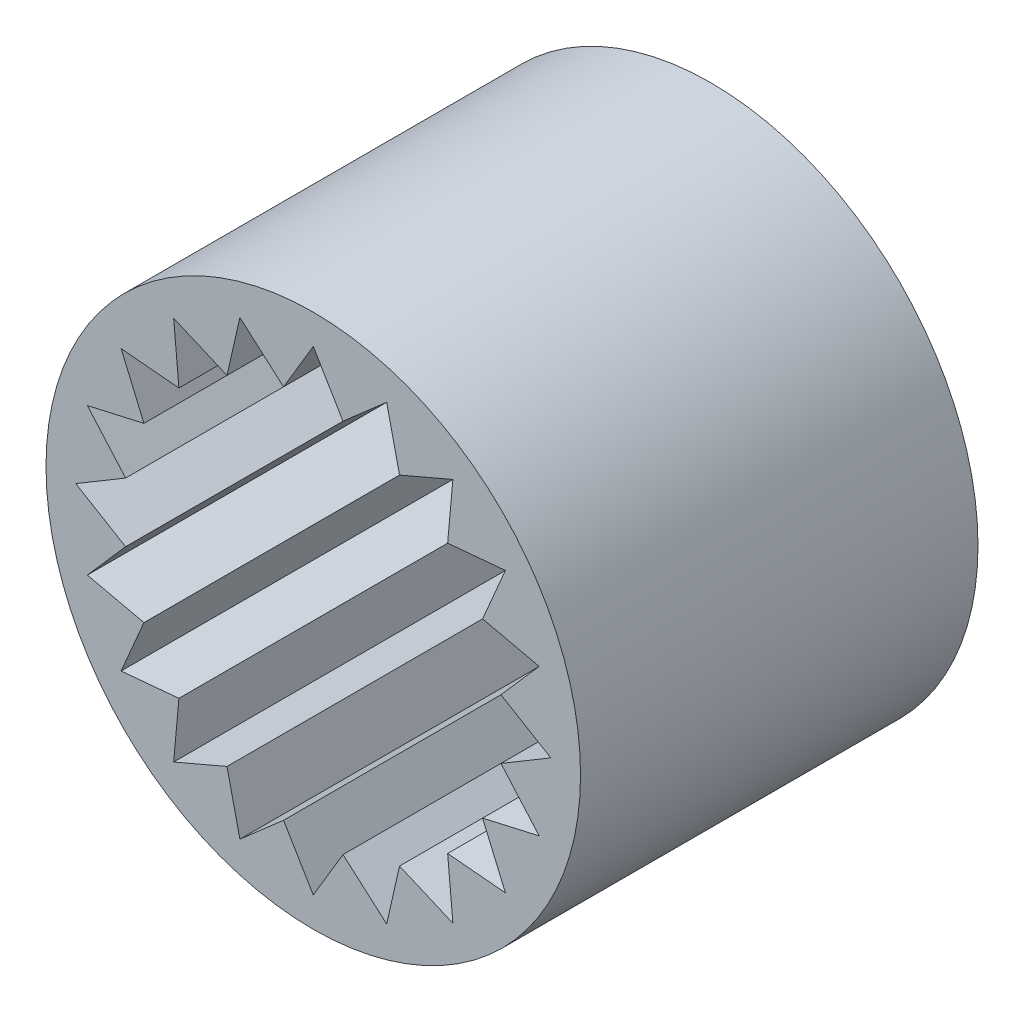
SolidWorks part; units mm, degrees
ref_plane "Front Plane" through (0, 0, 0) normal (0, 0, 1) x (1, 0, 0)
ref_plane "Top Plane" through (0, 0, 0) normal (0, 1, 0) x (1, 0, 0)
ref_plane "Right Plane" through (0, 0, 0) normal (1, 0, 0) x (0, 0, -1)
sketch "ServoSplineProfile" plane through (0, 0, 0) normal (0, 0, 1) x (1, 0, 0)
  line L0 (0, 0) -> (0, 2.5) construction
  line L1 (0, 0) -> (0.7725, 2.3776) construction
  line L2 (0, 0) -> (0.3911, 2.4692) construction
  line L3 (0, 2.5) -> (0.3129, 1.9754) construction
  line L4 (0.3129, 1.9754) -> (0.7725, 2.3776) construction
  line L5 (0.7725, 2.3776) -> (0.908, 1.782) construction
  line L6 (0.908, 1.782) -> (1.4695, 2.0225) construction
  line L7 (1.4695, 2.0225) -> (1.4142, 1.4142) construction
  line L8 (1.4142, 1.4142) -> (2.0225, 1.4695) construction
  line L9 (2.0225, 1.4695) -> (1.782, 0.908) construction
  line L10 (1.782, 0.908) -> (2.3776, 0.7725) construction
  line L11 (2.3776, 0.7725) -> (1.9754, 0.3129) construction
  line L12 (1.9754, 0.3129) -> (2.5, 0) construction
  line L13 (2.5, 0) -> (1.9754, -0.3129) construction
  line L14 (1.9754, -0.3129) -> (2.3776, -0.7725) construction
  line L15 (2.3776, -0.7725) -> (1.782, -0.908) construction
  line L16 (1.782, -0.908) -> (2.0225, -1.4695) construction
  line L17 (2.0225, -1.4695) -> (1.4142, -1.4142) construction
  line L18 (1.4142, -1.4142) -> (1.4695, -2.0225) construction
  line L19 (1.4695, -2.0225) -> (0.908, -1.782) construction
  line L20 (0.908, -1.782) -> (0.7725, -2.3776) construction
  line L21 (0.7725, -2.3776) -> (0.3129, -1.9754) construction
  line L22 (0.3129, -1.9754) -> (0, -2.5) construction
  line L23 (0, -2.5) -> (-0.3129, -1.9754) construction
  line L24 (-0.3129, -1.9754) -> (-0.7725, -2.3776) construction
  line L25 (-0.7725, -2.3776) -> (-0.908, -1.782) construction
  line L26 (-0.908, -1.782) -> (-1.4695, -2.0225) construction
  line L27 (-1.4695, -2.0225) -> (-1.4142, -1.4142) construction
  line L28 (-1.4142, -1.4142) -> (-2.0225, -1.4695) construction
  line L29 (-2.0225, -1.4695) -> (-1.782, -0.908) construction
  line L30 (-1.782, -0.908) -> (-2.3776, -0.7725) construction
  line L31 (-2.3776, -0.7725) -> (-1.9754, -0.3129) construction
  line L32 (-1.9754, -0.3129) -> (-2.5, 0) construction
  line L33 (-2.5, 0) -> (-1.9754, 0.3129) construction
  line L34 (-1.9754, 0.3129) -> (-2.3776, 0.7725) construction
  line L35 (-2.3776, 0.7725) -> (-1.782, 0.908) construction
  line L36 (-1.782, 0.908) -> (-2.0225, 1.4695) construction
  line L37 (-2.0225, 1.4695) -> (-1.4142, 1.4142) construction
  line L38 (-1.4142, 1.4142) -> (-1.4695, 2.0225) construction
  line L39 (-1.4695, 2.0225) -> (-0.908, 1.782) construction
  line L40 (-0.908, 1.782) -> (-0.7725, 2.3776) construction
  line L41 (-0.7725, 2.3776) -> (-0.3129, 1.9754) construction
  line L42 (-0.3129, 1.9754) -> (0, 2.5) construction
  line L43 (0.2147, 2.6281) -> (0.374, 2.361)
  line L44 (0.374, 2.361) -> (0.9234, 2.8418)
  line L45 (0.9234, 2.8418) -> (1.0853, 2.1299)
  line L46 (1.0853, 2.1299) -> (1.7564, 2.4174)
  line L47 (1.7564, 2.4174) -> (1.6903, 1.6903)
  line L48 (1.6903, 1.6903) -> (2.4174, 1.7564)
  line L49 (2.4174, 1.7564) -> (2.1299, 1.0853)
  line L50 (2.1299, 1.0853) -> (2.8418, 0.9234)
  line L51 (2.8418, 0.9234) -> (2.361, 0.374)
  line L52 (2.361, 0.374) -> (2.9881, 0)
  line L53 (2.9881, 0) -> (2.361, -0.374)
  line L54 (2.361, -0.374) -> (2.8418, -0.9234)
  line L55 (2.8418, -0.9234) -> (2.1299, -1.0853)
  line L56 (2.1299, -1.0853) -> (2.4174, -1.7564)
  line L57 (2.4174, -1.7564) -> (1.6903, -1.6903)
  line L58 (1.6903, -1.6903) -> (1.7564, -2.4174)
  line L59 (1.7564, -2.4174) -> (1.0853, -2.1299)
  line L60 (1.0853, -2.1299) -> (0.9234, -2.8418)
  line L61 (0.9234, -2.8418) -> (0.374, -2.361)
  line L62 (0.374, -2.361) -> (0, -2.9881)
  line L63 (0, -2.9881) -> (-0.374, -2.361)
  line L64 (-0.374, -2.361) -> (-0.9234, -2.8418)
  line L65 (-0.9234, -2.8418) -> (-1.0853, -2.1299)
  line L66 (-1.0853, -2.1299) -> (-1.7564, -2.4174)
  line L67 (-1.7564, -2.4174) -> (-1.6903, -1.6903)
  line L68 (-1.6903, -1.6903) -> (-2.4174, -1.7564)
  line L69 (-2.4174, -1.7564) -> (-2.1299, -1.0853)
  line L70 (-2.1299, -1.0853) -> (-2.8418, -0.9234)
  line L71 (-2.8418, -0.9234) -> (-2.361, -0.374)
  line L72 (-2.361, -0.374) -> (-2.9881, 0)
  line L73 (-2.9881, 0) -> (-2.361, 0.374)
  line L74 (-2.361, 0.374) -> (-2.8418, 0.9234)
  line L75 (-2.8418, 0.9234) -> (-2.1299, 1.0853)
  line L76 (-2.1299, 1.0853) -> (-2.4174, 1.7564)
  line L77 (-2.4174, 1.7564) -> (-1.6903, 1.6903)
  line L78 (-1.6903, 1.6903) -> (-1.7564, 2.4174)
  line L79 (-1.7564, 2.4174) -> (-1.0853, 2.1299)
  line L80 (-1.0853, 2.1299) -> (-0.9234, 2.8418)
  line L81 (-0.9234, 2.8418) -> (-0.374, 2.361)
  line L82 (-0.374, 2.361) -> (-0.2147, 2.6281)
  line L83 (-0.2147, 2.6281) -> (0, 2.9881)
  line L84 (0, 2.9881) -> (0.2147, 2.6281)
  circle A0 centre (0, 0) radius 2.5 construction
  circle A1 centre (0, 0) radius 2 construction
  circle A2 centre (0, 0) radius 2.25 construction
  circle A3 centre (0, 0) radius 3.3623
  point P7 (-1.7184, -1.4418)
  point P68 (0, 0)
  dimension "D1" = 5
  dimension "D4" = 4
  dimension "D2" = 18
  dimension "D3" = 9
  dimension "D6" = 0.25
  dimension "D5" = 20
extrude "ServoKey" add sketch "ServoSplineProfile" along normal blind 5
